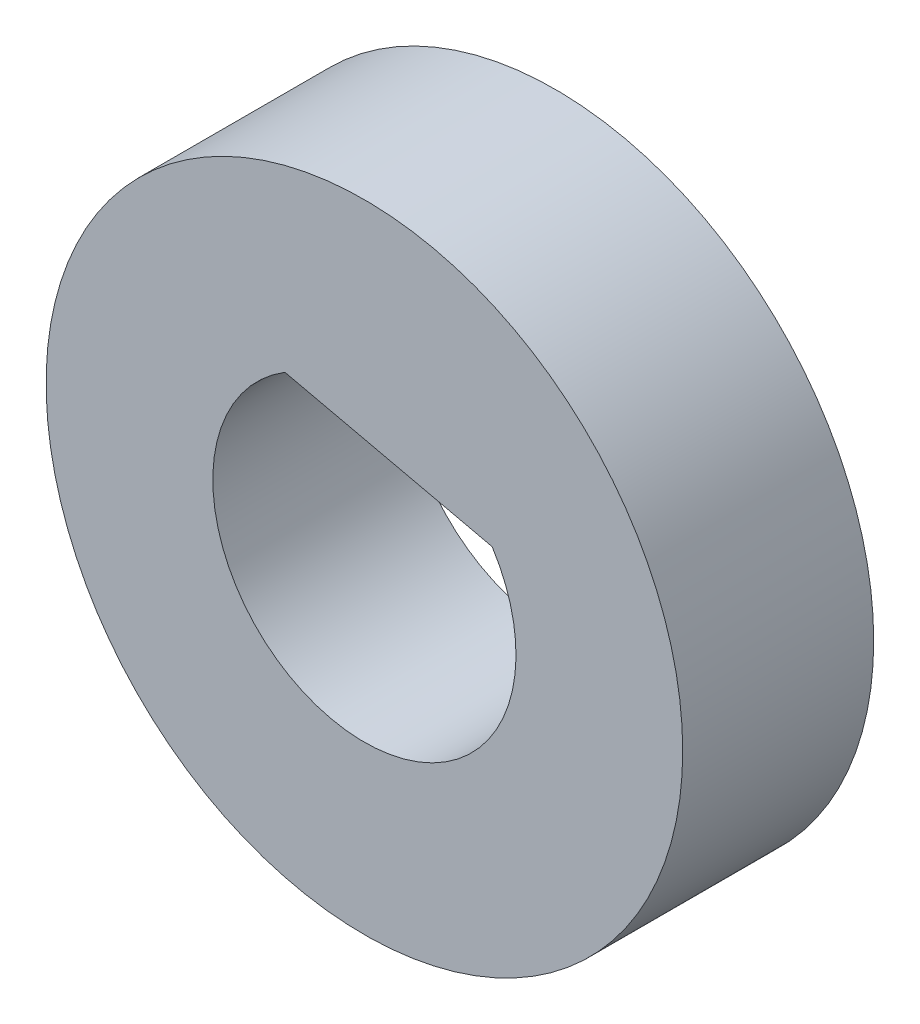
SolidWorks part; units mm, degrees
ref_plane "Front Plane" through (0, 0, 0) normal (0, 0, 1) x (1, 0, 0)
ref_plane "Top Plane" through (0, 0, 0) normal (0, 1, 0) x (1, 0, 0)
ref_plane "Right Plane" through (0, 0, 0) normal (1, 0, 0) x (0, 0, -1)
sketch "Sketch1" plane through (0, 0, 0) normal (0, 0, 1) x (1, 0, 0)
  circle A0 centre (0, 0) radius 5
  dimension "D1" = 10
extrude "Boss-Extrude1" add sketch "Sketch1" along normal blind 3
sketch "Sketch2" plane through (0, 0, 3) normal (0, 0, 1) x (1, 0, 0)
  line L0 (-1.2492, 2.0273) -> (2.0067, 1.282)
  arc A0 (-1.2492, 2.0273) -> (2.0067, 1.282) centre (0, 0) ccw
  dimension "D1" = 4.7625
  dimension "D2" = 2.0067
  dimension "D3" = 3.3401
extrude "Cut-Extrude1" cut sketch "Sketch2" against normal blind 3 contours A0 L0
equation "\"outer_diameter_spool\"=10"
equation "\"D1@Sketch1\"=\"outer_diameter_spool\""
equation "\"depth\"=3"
equation "\"D1@Boss-Extrude1\"=\"depth\""
equation "\"laser_offset\"= 0.125"
equation "\"diameter_shaft\"=4.7625"
equation "\"D1@Sketch2\"=\"diameter_shaft\""
equation "\"D1@Cut-Extrude1\"= \"depth\""
